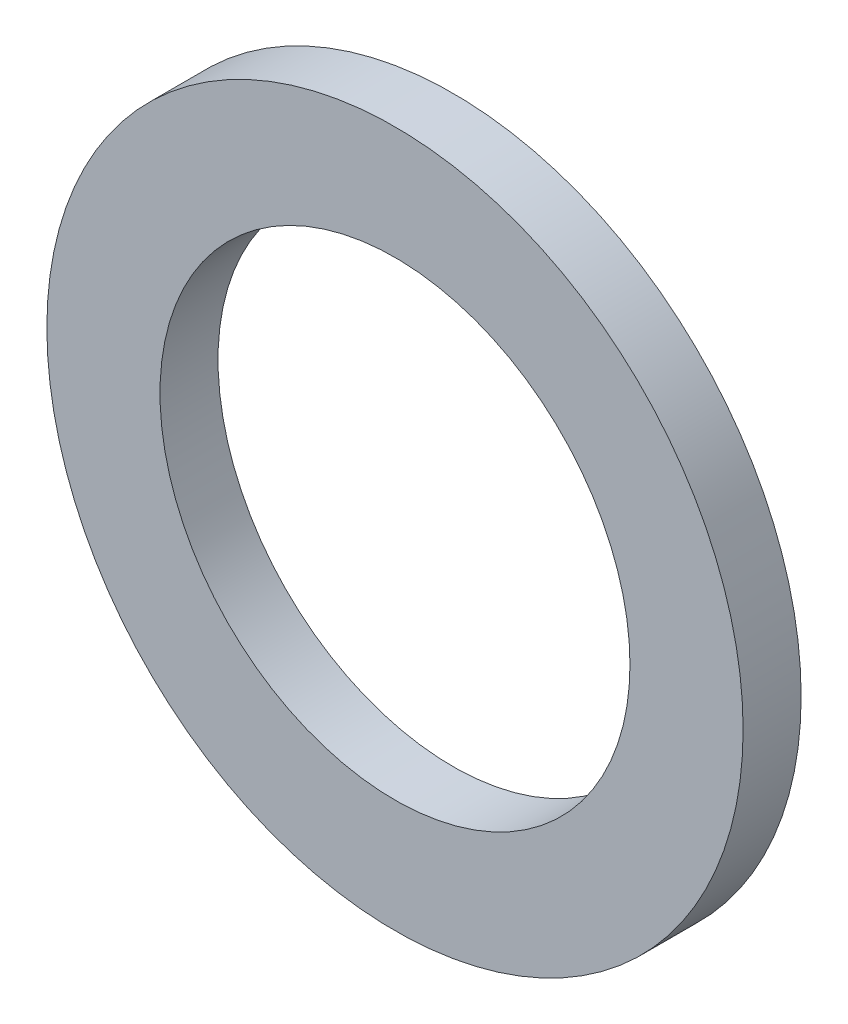
SolidWorks part; units mm, degrees
ref_plane "前视基准面" through (0, 0, 0) normal (0, 0, 1) x (1, 0, 0)
ref_plane "上视基准面" through (0, 0, 0) normal (0, 1, 0) x (1, 0, 0)
ref_plane "右视基准面" through (0, 0, 0) normal (1, 0, 0) x (0, 0, -1)
other "Configuration Table"
sketch "Profile_1" plane through (0, 0, 0) normal (0, 0, 1) x (1, 0, 0)
  circle A0 centre (0, 0) radius 6
  circle A1 centre (0, 0) radius 4.05
extrude "Thrust_ring" add sketch "Profile_1" along normal blind 1 from offset 0
